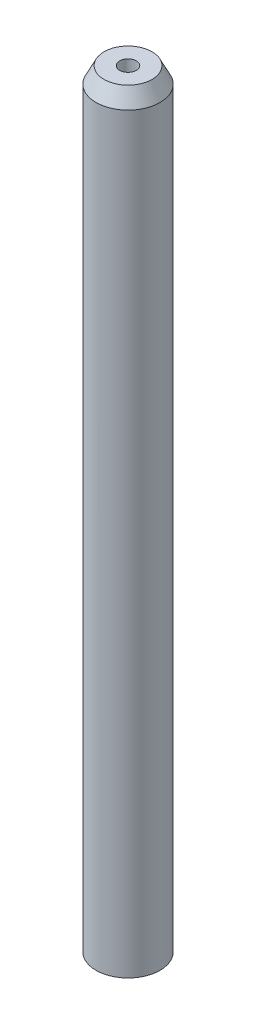
SolidWorks part; units mm, degrees
ref_plane "Front Plane" through (0, 0, 0) normal (0, 0, 1) x (1, 0, 0)
ref_plane "Top Plane" through (0, 0, 0) normal (0, 1, 0) x (1, 0, 0)
ref_plane "Right Plane" through (0, 0, 0) normal (1, 0, 0) x (0, 0, -1)
sketch "Sketch1" plane through (0, 0, 0) normal (0, 1, 0) x (1, 0, 0)
  circle A0 centre (0, 0) radius 6.35
  dimension "D1" = 12.7
extrude "PostBody" add sketch "Sketch1" along normal blind 152.4
sketch "Sketch4" plane through (0, 0, 0) normal (0, 0, 1) x (1, 0, 0)
  line L5 (6.35, 152.4) -> (6.35, 149.225)
  line L6 (6.35, 152.4) -> (-6.35, 152.4) construction
  line L7 (6.35, 0) -> (6.35, 152.4) construction
  line L8 (6.35, 149.225) -> (4.7625, 152.4)
  line L9 (4.7625, 152.4) -> (6.35, 152.4)
  dimension "D1" = 1.5875
  dimension "D2" = 3.175
sketch "Sketch5" plane through (0, 152.4, 0) normal (0, 1, 0) x (1, 0, 0)
  circle A0 centre (0, 0) radius 4.7487
sweep "TopCut" cut profiles "Sketch4" path "Sketch5"
hole_wizard "M4x0.7 Tapped Hole1" positions "Sketch6" profile "Sketch7" tap size "M4x0.7" standard "ANSI Metric"
sketch "Sketch6" plane through (0, 152.4, 0) normal (0, 1, 0) x (1, 0, 0)
  point P0 (0, 0)
sketch "Sketch7" plane through (0, 152.4, 0) normal (1, 0, 0) x (0, 0, 1)
  line L0 (0, 0) -> (0, 10.5164)
  line L1 (0, 10.5164) -> (1.65, 9.525)
  line L2 (1.65, 9.525) -> (1.65, 0)
  line L5 (1.65, 0) -> (0, 0)
  line L10 (0, 10.5164) -> (-1.65, 9.525) construction
  line L11 (0, -6.35) -> (0, 107.95) construction
  dimension "Tap Drill Dia." = 3.3
  dimension "Tap Drill Depth" = 9.525
  dimension "Drill Angle" = 118
cosmetic thread "Hole Thread2" parameters "D1"=7.874, "D2"=4
hole_wizard "M6x1.0 Tapped Hole1" positions "Sketch8" profile "Sketch9" tap size "M6x1.0" standard "ANSI Metric"
sketch "Sketch8" plane through (0, 0, 0) normal (0, -1, 0) x (-1, 0, 0)
  point P0 (0, 0)
sketch "Sketch9" plane through (0, 0, 0) normal (1, 0, 0) x (0, 0, -1)
  line L0 (0, 0) -> (0, 14.2022)
  line L1 (0, 14.2022) -> (2.5, 12.7)
  line L2 (2.5, 12.7) -> (2.5, 0)
  line L5 (2.5, 0) -> (0, 0)
  line L10 (0, 14.2022) -> (-2.5, 12.7) construction
  line L11 (0, -6.35) -> (0, 107.95) construction
  dimension "Tap Drill Dia." = 5
  dimension "Tap Drill Depth" = 12.7
  dimension "Drill Angle" = 118
cosmetic thread "Hole Thread1" parameters "D1"=11.938, "D2"=6
equation "\"post_diameter\"=0.5"
equation "\"D1@Sketch1\"=\"post_diameter\""
equation "\"post_height\"=6"
equation "\"D1@PostBody\" = \"post_height\""
